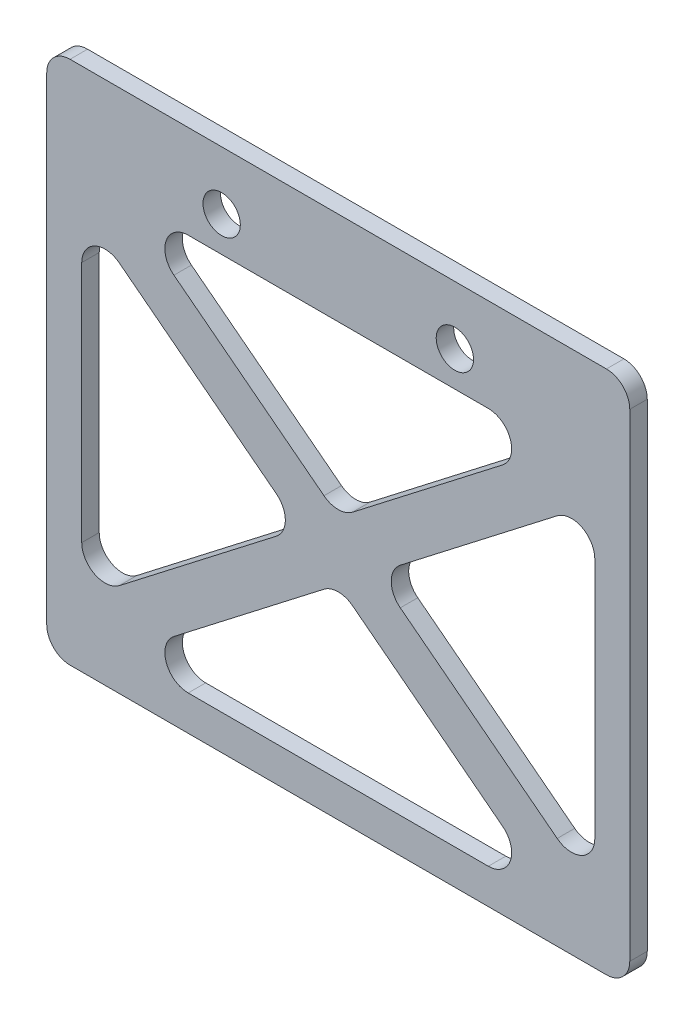
SolidWorks part; units mm, degrees
material "Thornel Mat VMA"
ref_plane "前视基准面" through (0, 0, 0) normal (0, 0, 1) x (1, 0, 0)
ref_plane "上视基准面" through (0, 0, 0) normal (0, 1, 0) x (1, 0, 0)
ref_plane "右视基准面" through (0, 0, 0) normal (1, 0, 0) x (0, 0, -1)
sketch "草图1" plane through (0, 0, 0) normal (0, 0, 1) x (1, 0, 0)
  line L1 (-25, 22.5) -> (25, 22.5)
  line L2 (-25, 22.5) -> (-25, -22.5)
  line L3 (-25, -22.5) -> (25, -22.5)
  line L4 (25, 22.5) -> (25, -22.5)
  line L5 (-25, 22.5) -> (25, -22.5) construction
  line L6 (-25, -22.5) -> (25, 22.5) construction
  point P0 (0, 0)
  dimension "D1" = 50
  dimension "D2" = 45
extrude "凸台-拉伸1" add sketch "草图1" along normal blind 1.5
sketch "草图2" plane through (0, 0, 0) normal (0, 0, -1) x (-1, 0, 0)
  line L0 (25, -22.5) -> (-25, -22.5) construction
  line L1 (-22, 14.5) -> (22, 14.5)
  line L2 (-22, 14.5) -> (-22, -19.5)
  line L3 (-22, -19.5) -> (22, -19.5)
  line L4 (22, 14.5) -> (22, -19.5)
  line L5 (-22, 14.5) -> (22, -19.5) construction
  line L6 (-22, -19.5) -> (22, 14.5) construction
  line L7 (25, 22.5) -> (25, -22.5) construction
  line L8 (-25, -22.5) -> (-25, 22.5) construction
  line L9 (-25, 22.5) -> (25, 22.5) construction
  line L10 (-23.2229, 12.9174) -> (20.7771, -21.0826)
  line L11 (-20.7771, -21.0826) -> (23.2229, 12.9174)
  line L12 (-20.7771, 16.0826) -> (23.2229, -17.9174)
  line L13 (-23.2229, -17.9174) -> (20.7771, 16.0826)
  circle A0 centre (10, 17.5) radius 1.5 construction
  circle A1 centre (-10, 17.5) radius 1.5 construction
  circle A2 centre (10, 17.5) radius 1.5 construction
  circle A3 centre (-10, 17.5) radius 1.5 construction
  circle A4 centre (10, 17.5) radius 1.6
  circle A5 centre (-10, 17.5) radius 1.6
  circle A6 centre (10, 17.5) radius 1.4 construction
  circle A7 centre (-10, 17.5) radius 1.4 construction
  point P6 (0, -2.5)
  point P21 (0, -22.5)
  point P38 (0, 8.4276)
  dimension "D3" = 3
  dimension "D4" = 3
  dimension "D5" = 3
  dimension "D6" = 8
  dimension "D1" = 0.1
  dimension "D2" = 0.1
  dimension "D7" = 2
  dimension "D8" = 2
extrude "切除-拉伸1" cut sketch "草图2" against normal blind 2 contours L12 L13 L1 | L2 L13 L10 | L11 L3 L10 | L11 L12 L4 | A5 | A4
fillet "圆角1" radius 2 16 edges at (-22, -16.9725, 0.75) (-3.2709, -2.5, 0.75) (-22, 11.9725, 0.75) (-18.7291, -19.5, 0.75) (18.7291, -19.5, 0.75) (0, -5.0275, 0.75) (25, -22.5, 0.75) (-25, -22.5, 0.75) (-25, 22.5, 0.75) (18.7291, 14.5, 0.75) (-18.7291, 14.5, 0.75) (0, 0.0275, 0.75) (22, 11.9725, 0.75) (3.2709, -2.5, 0.75) (22, -16.9725, 0.75) (25, 22.5, 0.75)
